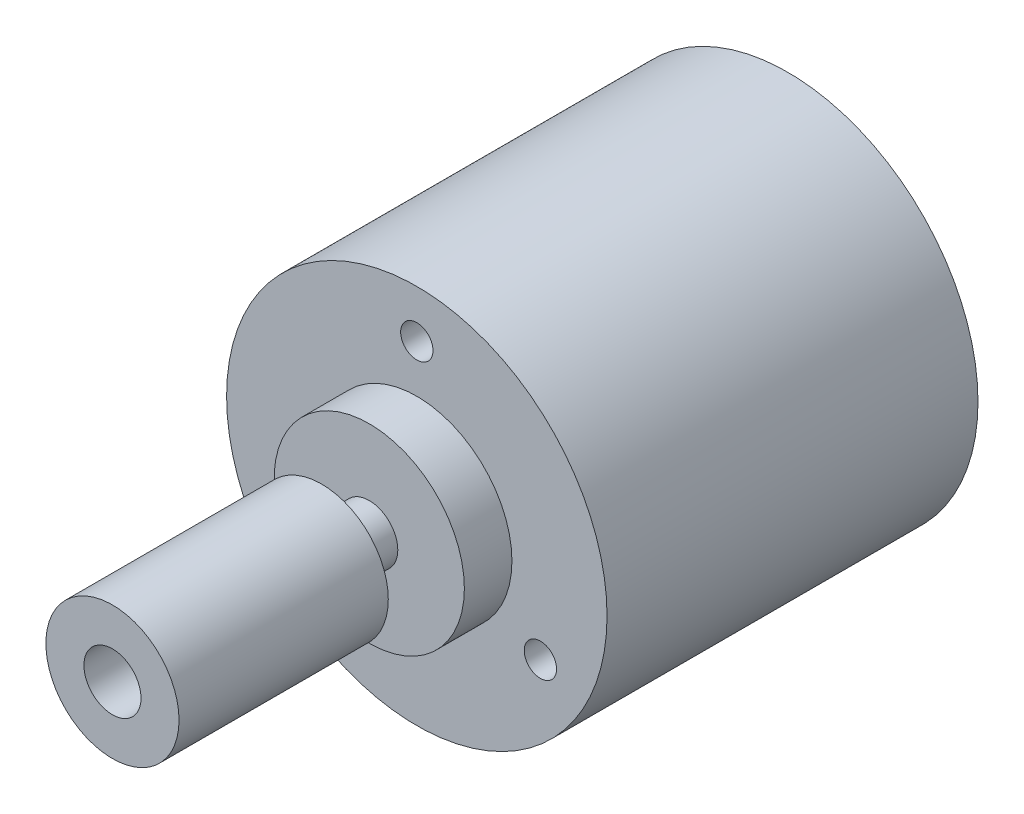
SolidWorks part; units mm, degrees
ref_plane "Front Plane" through (0, 0, 0) normal (0, 0, 1) x (1, 0, 0)
ref_plane "Top Plane" through (0, 0, 0) normal (0, 1, 0) x (1, 0, 0)
ref_plane "Right Plane" through (0, 0, 0) normal (1, 0, 0) x (0, 0, -1)
sketch "Sketch1" plane through (0, 0, 0) normal (0, 0, 1) x (1, 0, 0)
  circle A0 centre (0, 0) radius 20
  dimension "D1" = 40
extrude "Boss-Extrude1" add sketch "Sketch1" against normal blind 39
sketch "Sketch2" plane through (0, 0, 0) normal (0, 0, 1) x (1, 0, 0)
  circle A0 centre (0, 0) radius 10
  dimension "D1" = 20
extrude "Boss-Extrude2" add sketch "Sketch2" along normal blind 5
sketch "Sketch7" plane through (0, 0, 5) normal (0, 0, 1) x (1, 0, 0)
  circle A0 centre (0, 0) radius 3
  dimension "D1" = 6
extrude "Boss-Extrude3" add sketch "Sketch7" along normal blind 5
sketch "Sketch9" plane through (0, 0, 10) normal (0, 0, 1) x (1, 0, 0)
  line L0 (-2.2361, 2) -> (2.2361, 2)
  arc A0 (-2.2361, 2) -> (2.2361, 2) centre (0, 0) ccw
  point P5 (0, 3)
  dimension "D1" = 1
extrude "Boss-Extrude4" add sketch "Sketch9" along normal blind 10
hole_wizard "M3 Clearance Hole2" positions "Sketch13" profile "Sketch14" hole size "M3" standard "ANSI Metric"
sketch "Sketch13" plane through (0, 0, 0) normal (0, 0, 1) x (1, 0, 0)
  point P0 (0, 15)
  point P13 (12.9919, -7.4991)
  point P14 (-12.9889, -7.5009)
  point P15 (0.001, 0)
  dimension "D1" = 15
  dimension "D2" = 3
sketch "Sketch14" plane through (0, 15, 0) normal (1, 0, 0) x (0, -1, 0)
  line L0 (0, 0) -> (0, 8.0215)
  line L1 (0, 8.0215) -> (1.7, 7)
  line L2 (1.7, 7) -> (1.7, 0)
  line L5 (1.7, 0) -> (0, 0)
  line L10 (0, 8.0215) -> (-1.7, 7) construction
  line L11 (0, -6.35) -> (0, 107.95) construction
  dimension "Hole Dia." = 3.4
  dimension "Hole Depth" = 7
  dimension "Drill Angle" = 118
sketch "Sketch15" plane through (0, 0, 10) normal (0, 0, 1) x (1, 0, 0)
  line L0 (-2.2361, 2) -> (2.2361, 2)
  circle A0 centre (0, 0) radius 7
  arc A1 (-2.2361, 2) -> (2.2361, 2) centre (0, 0) ccw
  dimension "D1" = 4
  dimension "D2" = 6
extrude "Boss-Extrude9" add sketch "Sketch15" along normal blind 22
sketch "Sketch18" plane through (0, 0, 32) normal (0, 0, 1) x (1, 0, 0)
  circle A0 centre (0, 0) radius 3
extrude "Cut-Extrude3" cut sketch "Sketch18" against normal blind 12
